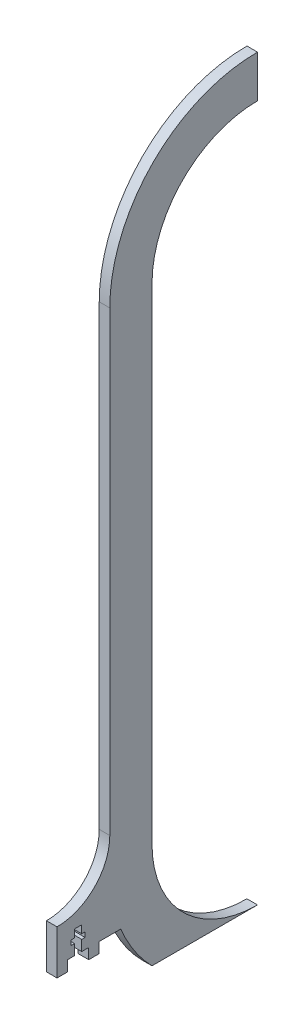
SolidWorks part; units mm, degrees
ref_plane "Front Plane" through (0, 0, 0) normal (0, 0, 1) x (1, 0, 0)
ref_plane "Top Plane" through (0, 0, 0) normal (0, 1, 0) x (1, 0, 0)
ref_plane "Right Plane" through (0, 0, 0) normal (1, 0, 0) x (0, 0, -1)
sketch "Elevator Ball Support Rail" plane through (0, 0, 0) normal (1, 0, 0) x (0, 0, -1)
  line L0 (63.5, 209.55) -> (63.5, 234.95)
  line L1 (63.5, 520.2476) -> (63.5, -209.55) construction
  line L2 (63.5, -209.55) -> (0, -209.55)
  line L3 (-31.75, -180.975) -> (-18.7887, -180.975)
  line L4 (-38.1, -187.325) -> (-31.75, -187.325)
  line L5 (-38.1, -180.975) -> (-38.1, -187.325)
  line L6 (0, 146.05) -> (0, -146.05)
  line L7 (-25.4, -128.905) -> (-25.4, -239.2791) construction
  line L8 (0, -146.05) -> (0, -313.4298) construction
  line L9 (-31.75, -180.975) -> (-31.75, -187.325)
  line L10 (-50.8, -180.975) -> (-46.609, -180.975)
  line L11 (-25.4, 146.05) -> (-25.4, -128.905)
  line L12 (-57.15, -160.655) -> (-57.15, -187.325)
  line L13 (-57.15, -187.325) -> (-50.8, -187.325)
  line L14 (-42.291, -180.975) -> (-38.1, -180.975)
  line L15 (-50.8, -187.325) -> (-50.8, -180.975)
  line L16 (-42.291, -174.625) -> (-42.291, -180.975)
  line L17 (-42.291, -174.625) -> (-40.25, -174.625)
  line L18 (-40.25, -174.625) -> (-40.25, -171.725)
  line L19 (-42.291, -171.725) -> (-42.291, -167.005)
  line L20 (-42.291, -167.005) -> (-46.609, -167.005)
  line L21 (-40.25, -171.725) -> (-42.291, -171.725)
  line L22 (-48.65, -171.725) -> (-48.65, -174.625)
  line L23 (-48.65, -174.625) -> (-46.609, -174.625)
  line L24 (-46.609, -174.625) -> (-46.609, -180.975)
  line L25 (-46.609, -167.005) -> (-46.609, -171.725)
  line L26 (-46.609, -171.725) -> (-48.65, -171.725)
  line L27 (0, -180.975) -> (101.6, -180.975) construction
  arc A0 (0, 146.05) -> (63.5, 209.55) centre (63.5, 146.05) cw
  arc A1 (63.5, 234.95) -> (-25.4, 146.05) centre (63.5, 146.05) ccw
  arc A2 (0, -146.05) -> (63.5, -209.55) centre (63.5, -146.05) ccw
  arc A3 (-18.7887, -180.975) -> (0, -209.55) centre (63.5, -147.333) ccw
  arc A4 (-57.15, -160.655) -> (-25.4, -128.905) centre (-57.15, -128.905) ccw
  point P4 (0, 0)
  dimension "D5" = 25.4
  dimension "D4" = 63.5
  dimension "D7" = 63.5
  dimension "D8" = 6.35
  dimension "D14" = 12.7
  dimension "D13" = 6.35
  dimension "D6" = 6.35
  dimension "D1" = 25.4
  dimension "D2" = 63.5
  dimension "D3" = 292.1
  dimension "D9" = 22.225
  dimension "D10" = 6.35
  dimension "D11" = 6.35
  dimension "D12" = 6.35
  dimension "D15" = 2.9
  dimension "D16" = 8.4
  dimension "D17" = 6.35
  dimension "D18" = 4.318
  dimension "D19" = 13.97
  dimension "D20" = 34.925
extrude "Boss-Extrude2" add sketch "Elevator Ball Support Rail" along normal blind 6.35 contours L5 L4 L9 L3 A3 L2 A2 L6 A0 L0 A1 L11 A4 L12 L13 L15 L10 L24 L23 L22 L26 L25 L20 L19 L21 L18 L17 L16 L14
equation "\"Ball Diameter\"= 1.75in"
equation "\"Pulley Diameter\" = 1in"
equation "\"Reactor Height\" = 14in"
equation "\"Sheet Thickness\"= 0.25in"
equation "\"Screw Diameter\"= .17in"
equation "\"Robot Diameter\"= 16in"
equation "\"Castor Screw Diameter\"= 0.22in"
equation "\"Wheel Diameter\" = 4in"
equation "\"Nut Diameter\" = 8.4mm"
equation "\"Nut Height\" = 2.9mm"
equation "\"Screw Height\" = 0.55in"
equation "\"D11@Elevator Ball Support Rail\"=\"Sheet Thickness\""
equation "\"Elevator Height\" = 11.5in"
equation "\"D12@Elevator Ball Support Rail\"=\"Sheet Thickness\""
equation "\"D7@Elevator Ball Support Rail\"=(\"Pulley Diameter\"/2) + \"Ball Diameter\" + 0.25in"
equation "\"D10@Elevator Ball Support Rail\"=\"Sheet Thickness\""
equation "\"D13@Elevator Ball Support Rail\"=\"Sheet Thickness\""
equation "\"D1@T-Slot\" = \"Screw Diameter\""
equation "\"D16@Elevator Ball Support Rail\"=\"Nut Diameter\""
equation "\"D15@Elevator Ball Support Rail\"=\"Nut Height\""
equation "\"D16@Elevator Ball Support Rail\" = \"Nut Diameter\""
equation "\"D9@Elevator Ball Support Rail\"=\"Ball Diameter\"/2"
equation "\"D1@Boss-Extrude2\"=\"Sheet Thickness\""
equation "\"D18@Elevator Ball Support Rail\"=\"Screw Diameter\""
equation "\"D19@Elevator Ball Support Rail\"=\"Screw Height\""
equation "\"D3@Elevator Ball Support Rail\"=\"Elevator Height\""
